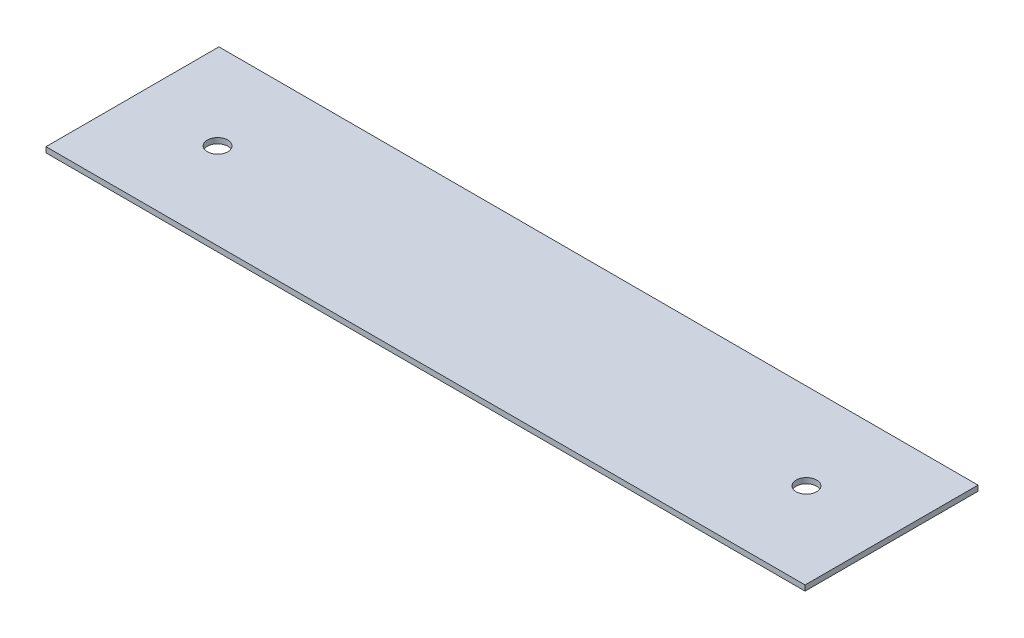
SolidWorks part; units mm, degrees
material "ASTM A36 Steel"
ref_plane "Front Plane" through (0, 0, 0) normal (0, 0, 1) x (1, 0, 0)
ref_plane "Top Plane" through (0, 0, 0) normal (0, 1, 0) x (1, 0, 0)
ref_plane "Right Plane" through (0, 0, 0) normal (1, 0, 0) x (0, 0, -1)
sketch "Sketch1" plane through (0, 0, 0) normal (0, 1, 0) x (1, 0, 0)
  line L0 (0, 101.6) -> (446, 101.6)
  line L2 (0, 0) -> (0, 101.6)
  line L5 (446, 101.6) -> (446, 0)
  line L6 (446, 0) -> (0, 0)
  dimension "D1" = 101.6
  dimension "D2" = 446
extrude "Boss-Extrude1" add sketch "Sketch1" along normal blind 3.175
sketch "Sketch2" plane through (0, 3.175, 0) normal (0, 1, 0) x (1, 0, 0)
  line L0 (346, 0) -> (100, 0) construction
  line L1 (0, 0) -> (446, 0) construction
  line L2 (446, 101.6) -> (0, 101.6) construction
  line L3 (100, 0) -> (100, 101.6) construction
  line L4 (346, 0) -> (346, 101.6) construction
  line L5 (0, 50.8) -> (44, 50.8) construction
  line L6 (0, 101.6) -> (0, 0) construction
  line L7 (346, 50.8) -> (390, 50.8) construction
  line L8 (446, 0) -> (446, 101.6) construction
  line L9 (56, 50.8) -> (100, 50.8) construction
  line L10 (402, 50.8) -> (446, 50.8) construction
  circle A0 centre (50, 50.8) radius 6
  circle A1 centre (396, 50.8) radius 6
  point P5 (223, 0)
  point P7 (223, 101.6)
  dimension "D2" = 12
  dimension "D1" = 123
extrude "Cut-Extrude1" cut sketch "Sketch2" against normal blind 10 contours A1 | A0
equation "\"grosor placa\"= ( 1in / 8 )"
equation "\"D1@Boss-Extrude1\"=\"grosor placa\""
equation "\"ancho\"=101.6"
equation "\"D1@Sketch1\"=\"ancho\""
equation "\"Largo\"= 246 + ( 100 * 2 )"
equation "\"D2@Sketch1\"=\"Largo\""
